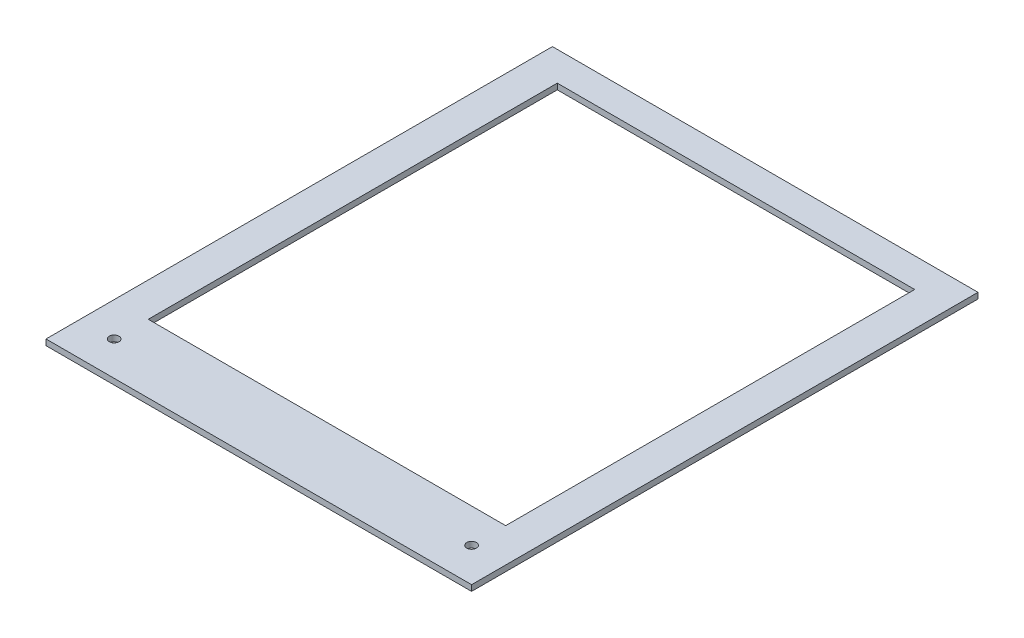
SolidWorks part; units mm, degrees
ref_plane "Front Plane" through (0, 0, 0) normal (0, 0, 1) x (1, 0, 0)
ref_plane "Top Plane" through (0, 0, 0) normal (0, 1, 0) x (1, 0, 0)
ref_plane "Right Plane" through (0, 0, 0) normal (1, 0, 0) x (0, 0, -1)
sketch "Sketch1" plane through (0, 0, 0) normal (0, 1, 0) x (1, 0, 0)
  line L0 (109.25, 120) -> (109.25, -140)
  line L1 (74.25, 105) -> (-74.25, 105)
  line L2 (0, 105) -> (0, 120)
  line L3 (74.25, -105) -> (-74.25, -105)
  line L4 (0, 120) -> (109.25, 120)
  line L5 (0, 120) -> (-109.25, 120)
  line L7 (109.25, -140) -> (-109.25, -140)
  line L8 (-109.25, 120) -> (-109.25, -140)
  line L9 (74.25, 105) -> (91.75, 105)
  line L10 (74.25, -105) -> (109.25, -140)
  line L11 (109.25, -140) -> (74.25, -140)
  line L12 (109.25, -140) -> (109.25, -105)
  line L13 (109.25, -105) -> (74.25, -105)
  line L14 (74.25, -140) -> (74.25, -105)
  line L15 (-74.25, -105) -> (-109.25, -105)
  line L16 (-74.25, -105) -> (-74.25, -140)
  line L17 (-74.25, -140) -> (-109.25, -140)
  line L18 (-109.25, -105) -> (-109.25, -140)
  line L19 (-74.25, -105) -> (-109.25, -140)
  line L20 (91.75, -105) -> (91.75, 120)
  line L21 (-91.75, -105) -> (-91.75, 120)
  line L25 (-109.25, 140) -> (-109.25, -140) construction
  line L26 (109.25, 140) -> (109.25, -140) construction
  line L27 (109.25, 140) -> (-109.25, 140) construction
  line L28 (91.75, 105) -> (91.75, -105)
  line L29 (74.25, -105) -> (-74.25, -105)
  line L30 (-91.75, -105) -> (-91.75, 105)
  line L31 (-91.75, 105) -> (-74.25, 105)
  line L33 (-74.25, 105) -> (-74.25, -105) construction
  line L34 (74.25, 105) -> (74.25, -105) construction
  circle A0 centre (-91.75, -122.5) radius 2.5
  circle A1 centre (91.75, -122.5) radius 2.5
  point P0 (0, 0)
  dimension "D4" = 210
  dimension "D1" = 35
  dimension "D2" = 218.5
extrude "Boss-Extrude1" add sketch "Sketch1" along normal blind 3 contours L21 L31 L1 L2 L5 | L9 L20 L4 L2 L1 | L20 L13 L0 L4 | L15 L21 L5 L8 | A0 L19 L7 L16 | A0 L19 L15 L8 | L3 L16 L7 L14 | A1 L10 L14 L7 | A1 L10 L0 L13
sketch "Sketch3" plane through (0, 3, 0) normal (0, 1, 0) x (1, 0, 0)
  line L0 (91.75, -105) -> (109.25, -105)
  line L3 (109.25, 120) -> (109.25, -140) construction
  line L4 (109.25, -105) -> (109.25, -115)
  line L5 (109.25, -115) -> (74.25, -115)
  line L6 (74.25, -115) -> (74.25, -105)
  line L7 (91.75, -105) -> (-91.75, -105) construction
  line L8 (74.25, -105) -> (91.75, -105)
  circle A0 centre (91.75, -122.5) radius 5.5
